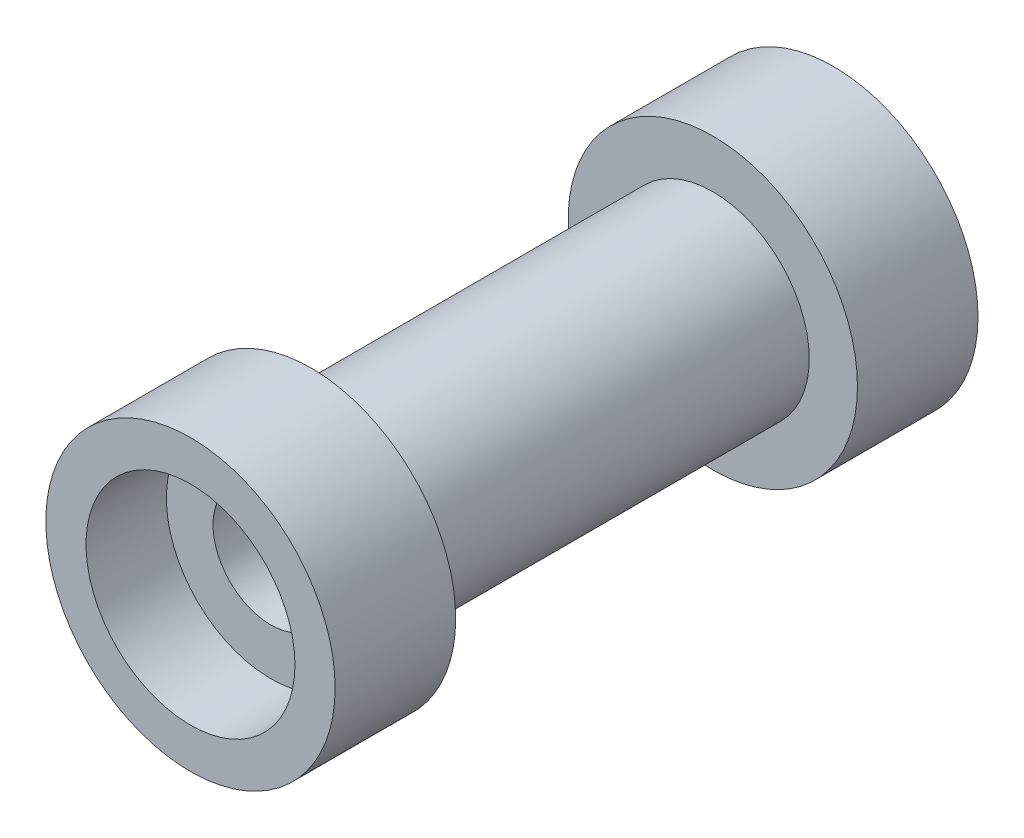
SolidWorks part; units mm, degrees
ref_plane "Front Plane" through (0, 0, 0) normal (0, 0, 1) x (1, 0, 0)
ref_plane "Top Plane" through (0, 0, 0) normal (0, 1, 0) x (1, 0, 0)
ref_plane "Right Plane" through (0, 0, 0) normal (1, 0, 0) x (0, 0, -1)
sketch "Sketch1" plane through (0, 0, 0) normal (0, 1, 0) x (1, 0, 0)
  line L0 (0, 0) -> (0, 20) construction
  line L1 (0, 0) -> (-9, 0) construction
  line L2 (-6, -12.5) -> (-6, 12.5)
  line L3 (-6, 12.5) -> (-9, 12.5)
  line L4 (-9, 12.5) -> (-9, 20)
  line L5 (-9, 20) -> (-6.5, 20)
  line L6 (-6.5, 20) -> (-6.5, 15)
  line L7 (-6.5, 15) -> (-3.6, 15)
  line L8 (-3.6, 15) -> (-3.6, -15)
  line L9 (-6.5, -15) -> (-3.6, -15)
  line L10 (-6.5, -20) -> (-6.5, -15)
  line L11 (-9, -20) -> (-6.5, -20)
  line L12 (-9, -12.5) -> (-9, -20)
  line L13 (-6, -12.5) -> (-9, -12.5)
  point P15 (-3.6, 0)
  point P20 (-6, 0)
  dimension "D1" = 6.5
  dimension "D2" = 5
  dimension "D3" = 9
  dimension "D4" = 3.6
  dimension "D5" = 7.5
  dimension "D6" = 12.5
  dimension "D7" = 6
revolve "Revolve1" add sketch "Sketch1" angle 360 about L0
